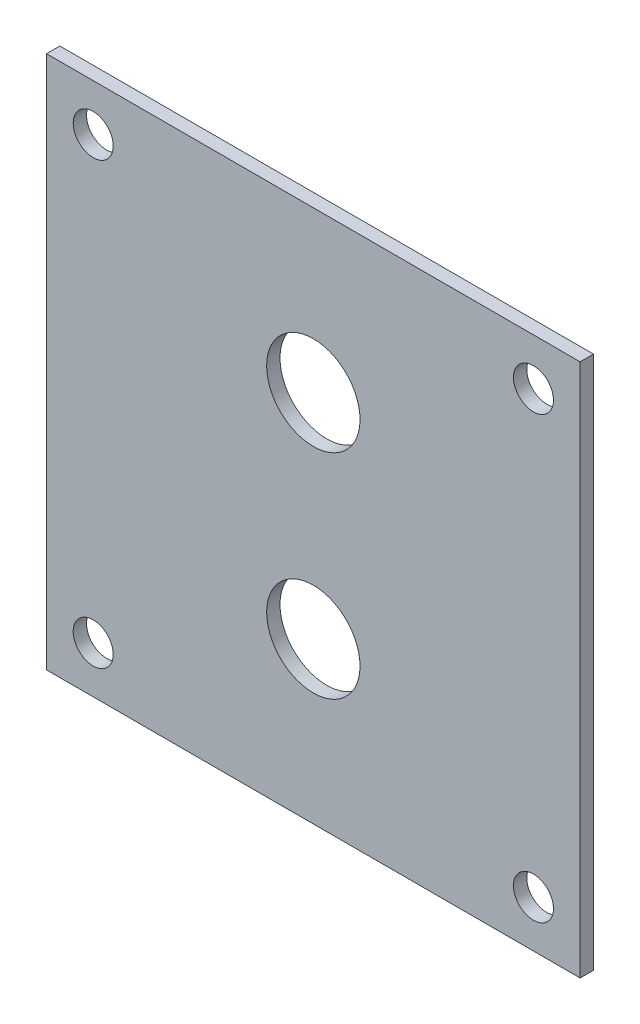
SolidWorks part; units mm, degrees
ref_plane "Front Plane" through (0, 0, 0) normal (0, 0, 1) x (1, 0, 0)
ref_plane "Top Plane" through (0, 0, 0) normal (0, 1, 0) x (1, 0, 0)
ref_plane "Right Plane" through (0, 0, 0) normal (1, 0, 0) x (0, 0, -1)
sketch "Sketch1" plane through (0, 0, 0) normal (0, 0, 1) x (1, 0, 0)
  line L1 (-63.5, 63.5) -> (63.5, 63.5)
  line L2 (-63.5, 63.5) -> (-63.5, -63.5)
  line L3 (-63.5, -63.5) -> (63.5, -63.5)
  line L4 (63.5, 63.5) -> (63.5, -63.5)
  line L5 (-63.5, 63.5) -> (63.5, -63.5) construction
  line L6 (-63.5, -63.5) -> (63.5, 63.5) construction
  point P0 (0, 0)
  dimension "D1" = 127
  dimension "D2" = 127
extrude "Boss-Extrude1" add sketch "Sketch1" along normal blind 3.175
sketch "Sketch2" plane through (0, 0, 0) normal (0, 0, -1) x (-1, 0, 0)
  line L4 (-63.5, 63.5) -> (63.5, 63.5) construction
  line L5 (63.5, -63.5) -> (-63.5, -63.5) construction
  line L6 (-63.5, -63.5) -> (-63.5, 63.5) construction
  circle A0 centre (0, 25.4) radius 11.1125
  circle A2 centre (0, -25.4) radius 11.1125
  dimension "D1" = 22.225
  dimension "D2" = 38.1
  dimension "D6" = 63.5
  dimension "D7" = 22.225
  dimension "D8" = 63.5
  dimension "D3" = 38.1
extrude "Cut-Extrude1" cut sketch "Sketch2" against normal up to surface (3.175 mm away) up to face at (0, 0, 3.175)
sketch "Sketch4" plane through (0, 0, 0) normal (0, 0, -1) x (-1, 0, 0)
  line L0 (63.5, 63.5) -> (63.5, -63.5) construction
  line L1 (-63.5, 63.5) -> (63.5, 63.5) construction
  line L2 (63.5, 0) -> (-63.5, 0) construction
  line L3 (-63.5, -63.5) -> (-63.5, 63.5) construction
  line L4 (0, -63.5) -> (0, 63.5) construction
  line L5 (63.5, -63.5) -> (-63.5, -63.5) construction
  circle A0 centre (52.3875, 52.3875) radius 4.7625
  circle A1 centre (52.3875, -52.3875) radius 4.7625
  circle A2 centre (-52.3875, 52.3875) radius 4.7625
  circle A3 centre (-52.3875, -52.3875) radius 4.7625
  dimension "D1" = 9.525
  dimension "D2" = 11.1125
  dimension "D3" = 11.1125
extrude "Cut-Extrude3" cut sketch "Sketch4" against normal up to surface (3.175 mm away) up to face at (11.1125, -25.4, 3.175)
